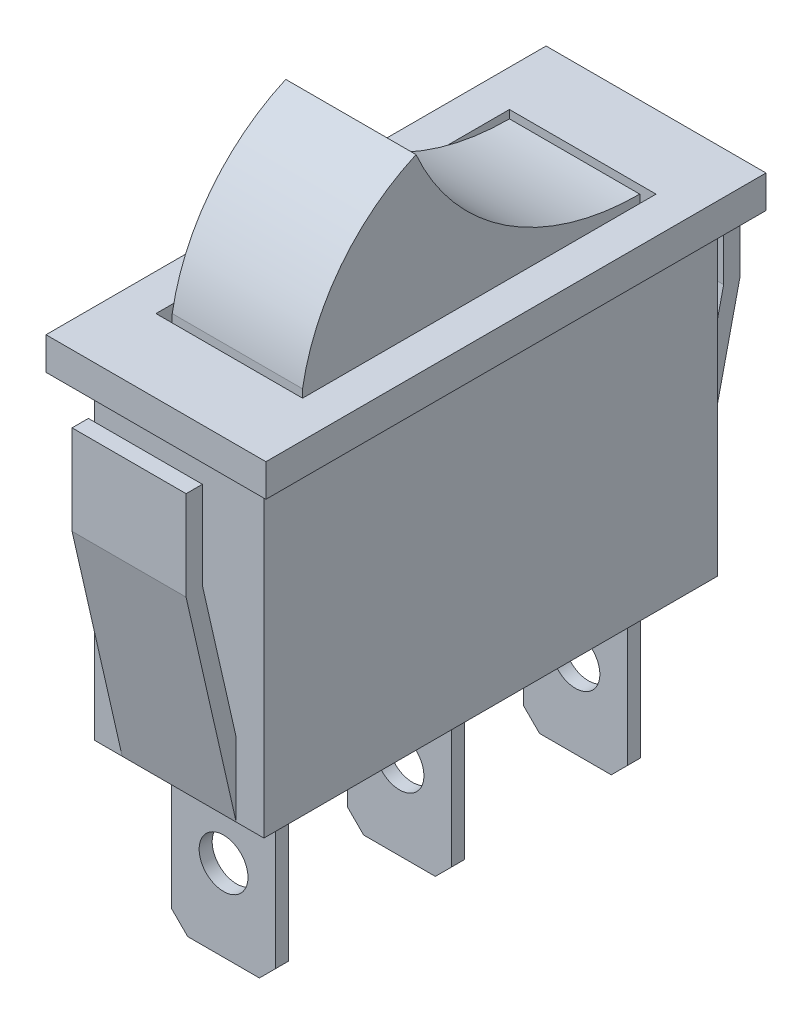
SolidWorks part; units mm, degrees
ref_plane "Plano frontal" through (0, 0, 0) normal (0, 0, 1) x (1, 0, 0)
ref_plane "Plano superior" through (0, 0, 0) normal (0, 1, 0) x (1, 0, 0)
ref_plane "Plano direito" through (0, 0, 0) normal (1, 0, 0) x (0, 0, -1)
sketch "Esboço1" plane through (0, 0, 0) normal (1, 0, 0) x (0, 0, -1)
  line L0 (0, 0) -> (27.8461, 0)
  line L1 (27.8461, 0) -> (30.9231, 13.5)
  line L2 (30.9231, 13.5) -> (30.9231, 19)
  line L3 (30.9231, 19) -> (29.9231, 19)
  line L4 (29.9231, 19) -> (29.9231, 13.6125)
  line L5 (29.9231, 13.6125) -> (27.8461, 4.5)
  line L6 (27.8461, 4.5) -> (27.8461, 19.5)
  line L7 (27.8461, 19.5) -> (29.2731, 19.5)
  line L8 (29.2731, 19.5) -> (29.2731, 21.5)
  line L9 (29.2731, 21.5) -> (24.2731, 21.5)
  line L10 (-1.4269, 21.5) -> (-1.4269, 19.5)
  line L11 (-1.4269, 19.5) -> (0, 19.5)
  line L12 (0, 19.5) -> (0, 4.5)
  line L13 (0, 4.5) -> (-2.0769, 13.6125)
  line L14 (-2.0769, 13.6125) -> (-2.0769, 19)
  line L15 (-2.0769, 19) -> (-3.0769, 19)
  line L16 (-3.0769, 19) -> (-3.0769, 13.5)
  line L17 (-3.0769, 13.5) -> (0, 0)
  line L18 (3.5731, 21.5) -> (-1.4269, 21.5)
  arc A0 (10.5389, 30.469) -> (24.2731, 21.5) centre (24.2731, 36.5) ccw
  arc A1 (10.5389, 30.469) -> (3.5731, 21.5) centre (15.4052, 19.5) ccw
  point P11 (0, 0)
  point P20 (0, 0)
  point P21 (0, 0)
  dimension "D11" = 24
  dimension "D12" = 30
  dimension "D13" = 15
  dimension "D14" = 5
  dimension "D1" = 30.7
  dimension "D2" = 2
  dimension "D3" = 34
  dimension "D4" = 19
  dimension "D5" = 4.5
  dimension "D6" = 1
  dimension "D8" = 5.5
  dimension "D9" = 1
  dimension "D10" = 21.5
extrude "Ressalto-extrusão2" add sketch "Esboço1" along normal mid plane 13.5
sketch "Esboço3" plane through (6.75, 0, 0) normal (1, 0, 0) x (0, 0, -1)
  line L1 (3.5731, 21.5) -> (24.2731, 21.5)
  line L2 (3.5731, 21.5) -> (3.5731, 30.469)
  line L3 (3.5731, 30.469) -> (24.2731, 30.469)
  line L4 (24.2731, 21.5) -> (24.2731, 30.469)
  point P5 (0, 0)
extrude "Corte-extrusão1" cut sketch "Esboço3" against normal blind 2.75
sketch "Esboço4" plane through (-6.75, 0, 0) normal (-1, 0, 0) x (0, 0, 1)
  line L1 (-3.5731, 21.5) -> (-24.2731, 21.5)
  line L2 (-3.5731, 21.5) -> (-3.5731, 30.469)
  line L3 (-3.5731, 30.469) -> (-24.2731, 30.469)
  line L4 (-24.2731, 21.5) -> (-24.2731, 30.469)
extrude "Corte-extrusão2" cut sketch "Esboço4" against normal blind 2.75
sketch "Esboço5" plane through (-6.75, 0, 0) normal (-1, 0, 0) x (0, 0, 1)
  line L0 (3.0769, 19) -> (3.0769, 13.5) construction
  line L1 (-30.9231, 19.5) -> (3.0769, 19.5)
  line L2 (-30.9231, 19.5) -> (-30.9231, 0)
  line L3 (-30.9231, 0) -> (3.0769, 0)
  line L4 (3.0769, 19.5) -> (3.0769, 0)
  line L5 (-30.9231, 13.5) -> (-30.9231, 19) construction
  line L6 (-27.8461, 19.5) -> (-29.2731, 19.5) construction
  line L7 (0, 0) -> (-27.8461, 0) construction
extrude "Corte-extrusão3" cut sketch "Esboço5" against normal blind 1.55
sketch "Esboço6" plane through (6.75, 0, 0) normal (1, 0, 0) x (0, 0, -1)
  line L0 (0, 0) -> (27.8461, 0) construction
  line L1 (-3.0769, 19.5) -> (30.9231, 19.5)
  line L2 (-3.0769, 19.5) -> (-3.0769, 0)
  line L3 (-3.0769, 0) -> (30.9231, 0)
  line L4 (30.9231, 19.5) -> (30.9231, 0)
  line L5 (-1.4269, 19.5) -> (0, 19.5) construction
  line L6 (-3.0769, 19) -> (-3.0769, 13.5) construction
  line L7 (30.9231, 13.5) -> (30.9231, 19) construction
extrude "Corte-extrusão4" cut sketch "Esboço6" against normal blind 1.55
sketch "Esboço8" plane through (5.2, 0, 0) normal (1, 0, 0) x (0, 0, -1)
  line L1 (-3.0769, 19) -> (0, 19)
  line L2 (-3.0769, 19) -> (-3.0769, 0)
  line L3 (-3.0769, 0) -> (0, 0)
  line L4 (0, 19) -> (0, 0)
  line L5 (30.9231, 19) -> (27.8461, 19)
  line L6 (30.9231, 19) -> (30.9231, 0)
  line L7 (30.9231, 0) -> (27.8461, 0)
  line L8 (27.8461, 19) -> (27.8461, 0)
extrude "Corte-extrusão5" cut sketch "Esboço8" against normal blind 1.7
sketch "Esboço9" plane through (-5.2, 0, 0) normal (-1, 0, 0) x (0, 0, 1)
  line L1 (-30.9231, 19) -> (-27.8461, 19)
  line L2 (-30.9231, 19) -> (-30.9231, 0)
  line L3 (-30.9231, 0) -> (-27.8461, 0)
  line L4 (-27.8461, 19) -> (-27.8461, 0)
  line L5 (3.0769, 19) -> (0, 19)
  line L6 (3.0769, 19) -> (3.0769, 0)
  line L7 (3.0769, 0) -> (0, 0)
  line L8 (0, 19) -> (0, 0)
extrude "Corte-extrusão6" cut sketch "Esboço9" against normal blind 1.7
sketch "Esboço10" plane through (0, 21.5, 0) normal (0, 1, 0) x (1, 0, 0)
  line L0 (4, 10.5389) -> (4, 24.2731) construction
  line L1 (-4.5, 3.0731) -> (4.5, 3.0731)
  line L2 (-4.5, 3.0731) -> (-4.5, 24.7731)
  line L3 (-4.5, 24.7731) -> (4.5, 24.7731)
  line L4 (4.5, 3.0731) -> (4.5, 24.7731)
  line L5 (-4, 24.2731) -> (-4, 10.5389) construction
  line L6 (4, 24.2731) -> (-4, 24.2731) construction
  line L7 (4, 3.5731) -> (-4, 3.5731) construction
  line L9 (-4, 24.2731) -> (4, 24.2731)
  line L10 (-4, 24.2731) -> (-4, 3.5731)
  line L11 (-4, 3.5731) -> (4, 3.5731)
  line L12 (4, 24.2731) -> (4, 3.5731)
  dimension "D1" = 0.5
  dimension "D2" = 0.5
  dimension "D3" = 0.5
  dimension "D4" = 0.5
extrude "Corte-extrusão7" cut sketch "Esboço10" against normal blind 1
sketch "Esboço11" plane through (0, 0, 0) normal (0, -1, 0) x (1, 0, 0)
  line L0 (0, -3.5231) -> (0, -13.5231) construction
  line L1 (-3.2, -2.7231) -> (3.2, -2.7231)
  line L2 (-3.2, -2.7231) -> (-3.2, -3.5231)
  line L3 (-3.2, -3.5231) -> (3.2, -3.5231)
  line L4 (3.2, -2.7231) -> (3.2, -3.5231)
  line L5 (-3.2, -13.5231) -> (3.2, -13.5231)
  line L6 (-3.2, -13.5231) -> (-3.2, -14.3231)
  line L7 (-3.2, -14.3231) -> (3.2, -14.3231)
  line L8 (3.2, -13.5231) -> (3.2, -14.3231)
  line L9 (-3.2, -24.3231) -> (3.2, -24.3231)
  line L10 (-3.2, -24.3231) -> (-3.2, -25.1231)
  line L11 (-3.2, -25.1231) -> (3.2, -25.1231)
  line L12 (3.2, -24.3231) -> (3.2, -25.1231)
  line L13 (0, -14.3231) -> (0, -24.3231) construction
  line L14 (0, 0) -> (0, -2.7231) construction
  line L16 (0, -25.1231) -> (0, -27.8461) construction
  line L18 (3.5, -27.8461) -> (-3.5, -27.8461) construction
  point P12 (0, -2.7231)
  dimension "D1" = 0.8
  dimension "D2" = 10
  dimension "D3" = 6.4
extrude "Ressalto-extrusão3" add sketch "Esboço11" along normal blind 10.3
sketch "Esboço12" plane through (0, 0, -25.1231) normal (0, 0, -1) x (-1, 0, 0)
  line L0 (3.2, -10.3) -> (-3.2, -10.3) construction
  circle A0 centre (0, -5.3) radius 1.5
  point P4 (0, 0)
  dimension "D1" = 3
  dimension "D2" = 5
extrude "Corte-extrusão8" cut sketch "Esboço12" against normal through all
chamfer "Chanfro1" distance 1 angle 45 6 edges at (-3.2, -10.3, -3.1231) (3.2, -10.3, -3.1231) (3.2, -10.3, -13.9231) (-3.2, -10.3, -13.9231) (-3.2, -10.3, -24.7231) (3.2, -10.3, -24.7231)
